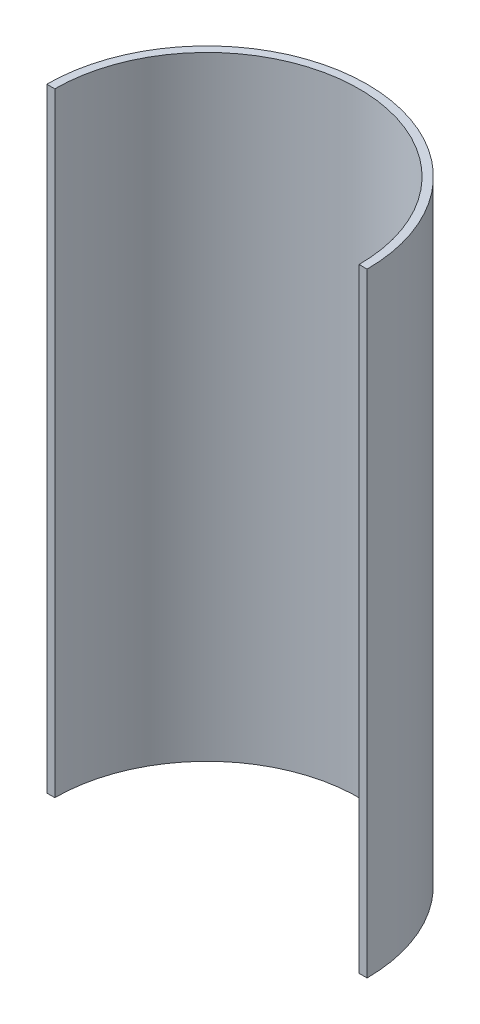
SolidWorks part; units mm, degrees
ref_plane "Front Plane" through (0, 0, 0) normal (0, 0, 1) x (1, 0, 0)
ref_plane "Top Plane" through (0, 0, 0) normal (0, 1, 0) x (1, 0, 0)
ref_plane "Right Plane" through (0, 0, 0) normal (1, 0, 0) x (0, 0, -1)
sketch "Sketch1" plane through (0, 0, 0) normal (0, 1, 0) x (1, 0, 0)
  line L0 (-60, 0) -> (-57, 0)
  line L1 (57, 0) -> (60, 0)
  arc A0 (60, 0) -> (-60, 0) centre (0, 0) ccw
  arc A1 (57, 0) -> (-57, 0) centre (0, 0) ccw
  circle A2 centre (0, 0) radius 60 construction
  circle A3 centre (0, 0) radius 57 construction
  dimension "D1" = 3
extrude "Boss-Extrude1" add sketch "Sketch1" along normal blind 230
